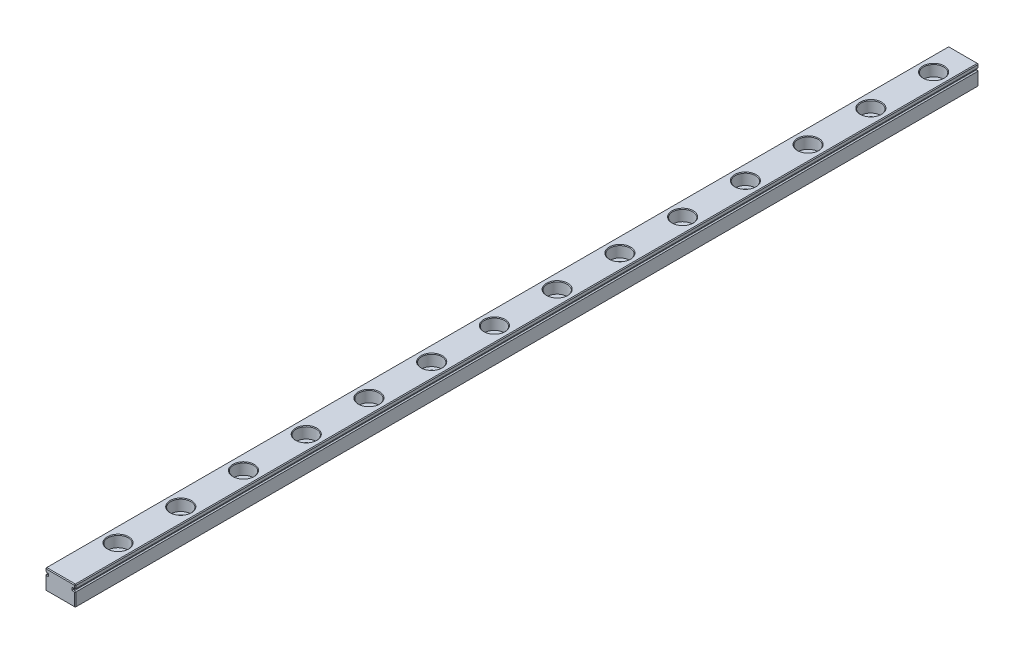
SolidWorks part; units mm, degrees
material "AISI 304"
ref_plane "Front Plane" through (0, 0, 0) normal (0, 0, 1) x (1, 0, 0)
ref_plane "Top Plane" through (0, 0, 0) normal (0, 1, 0) x (1, 0, 0)
ref_plane "Right Plane" through (0, 0, 0) normal (1, 0, 0) x (0, 0, -1)
sketch "Sketch1" plane through (0, 0, 0) normal (0, 0, 1) x (1, 0, 0)
  line L0 (0, 0) -> (0, 8) construction
  line L1 (0, 8) -> (12, 8)
  line L2 (0, 0) -> (12, 0)
  line L3 (0, 8) -> (0, 6.75)
  line L4 (0, 6.75) -> (0.5, 6.25) construction
  line L5 (0.5, 6.25) -> (1, 6.25)
  line L6 (0.5, 5.75) -> (0, 5.25) construction
  line L7 (0, 5.25) -> (0, 0)
  line L8 (1, 6.25) -> (1, 5.75)
  line L9 (1, 5.75) -> (0.5, 5.75)
  line L10 (0.5, 5.75) -> (0.75, 6) construction
  line L11 (0.75, 6) -> (0.5, 6.25) construction
  line L12 (0, 6.75) -> (0, 6.559)
  line L13 (0, 5.25) -> (0, 5.441)
  line L14 (6, 8) -> (6, 0) construction
  line L15 (11.25, 6) -> (11.5, 6.25) construction
  line L16 (11.5, 5.75) -> (11.25, 6) construction
  line L17 (11.5, 5.75) -> (12, 5.25) construction
  line L18 (12, 6.75) -> (11.5, 6.25) construction
  line L19 (12, 0) -> (12, 8) construction
  line L20 (12, 5.25) -> (12, 5.441)
  line L21 (12, 6.75) -> (12, 6.559)
  line L22 (11, 5.75) -> (11.5, 5.75)
  line L23 (11, 6.25) -> (11, 5.75)
  line L24 (12, 5.25) -> (12, 0)
  line L25 (11.5, 6.25) -> (11, 6.25)
  line L26 (12, 8) -> (12, 6.75)
  arc A0 (0, 5.441) -> (0.5, 5.75) centre (0, 6) ccw
  arc A1 (0.5, 6.25) -> (0, 6.559) centre (0, 6) ccw
  arc A2 (11.5, 6.25) -> (12, 6.559) centre (12, 6) cw
  arc A3 (12, 5.441) -> (11.5, 5.75) centre (12, 6) cw
  point P4 (1, 6)
  point P28 (11, 6)
  dimension "D1" = 8
  dimension "D2" = 6
  dimension "D3" = 0.5
  dimension "D4" = 45
  dimension "D5" = 2
  dimension "D6" = 1
extrude "Boss-Extrude1" add sketch "Sketch1" along normal blind 360
chamfer "Chamfer1" distance 0.3 angle 45 36 edges at (0, 0, 180) (12, 0, 180) (0, 8, 180) (12, 8, 180) (0.2939, 5.5245, 360) (0.75, 5.75, 360) (1, 6, 360) (0.75, 6.25, 360) (0.2939, 6.4755, 360) (0, 7.2795, 360) (6, 8, 360) (12, 7.2795, 360) (11.7061, 6.4755, 360) (11.25, 6.25, 360) (11, 6, 360) (11.25, 5.75, 360) (11.7061, 5.5245, 360) (12, 2.7205, 360) (6, 0, 360) (0, 2.7205, 360) (12, 2.7205, 0) (11.7061, 5.5245, 0) (11.25, 5.75, 0) (11, 6, 0) (11.25, 6.25, 0) (11.7061, 6.4755, 0) (12, 7.2795, 0) (6, 0, 0) (0, 2.7205, 0) (0.2939, 5.5245, 0) (0.75, 5.75, 0) (1, 6, 0) (0.75, 6.25, 0) (0.2939, 6.4755, 0) (0, 7.2795, 0) (6, 8, 0)
hole_wizard "CBORE for M5 Hex Head Bolt1" positions "3DSketch1" profile "Sketch3" counterbore size "M5" standard "ANSI Metric" end condition through all
sketch3d "3DSketch1"
  line L0 (6, 8, 0) -> (6, 8, 12) construction
  line L1 (11.7, 8, 0) -> (0.3, 8, 0) construction
  point P0 (6, 8, 12)
  dimension "D1" = 12
sketch "Sketch3" plane through (6, 8, 12) normal (1, 0, 0) x (0, 0, 1)
  line L0 (0, 0) -> (0, 8)
  line L1 (2.25, 7.75) -> (2.5, 8)
  line L2 (4, 4.5) -> (2.25, 4.5)
  line L3 (2.25, 4.5) -> (2.25, 7.75)
  line L5 (4, 4.5) -> (4, 0.25)
  line L6 (4, 0.25) -> (4.25, 0)
  line L7 (4.25, 0) -> (0, 0)
  line L8 (-4, 0.25) -> (-4.25, 0) construction
  line L11 (0, -6.35) -> (0, 107.95) construction
  line L12 (2.5, 8) -> (0, 8)
  line L13 (-2.25, 7.75) -> (-2.5, 8) construction
  dimension "Thru Hole Dia." = 4.5
  dimension "Thru Hole Depth" = 8
  dimension "C'Bore Dia." = 8
  dimension "C'Bore Depth" = 4.5
  dimension "Near C'Sink Dia." = 8.5
  dimension "Near C'Sink Angle" = 90
  dimension "Far C'Sink Dia." = 5
  dimension "Far C'Sink Angle" = 90
pattern_linear "LPattern1" count 14 spacing 25 along (0, 0, 1) of "CBORE for M5 Hex Head Bolt1"
